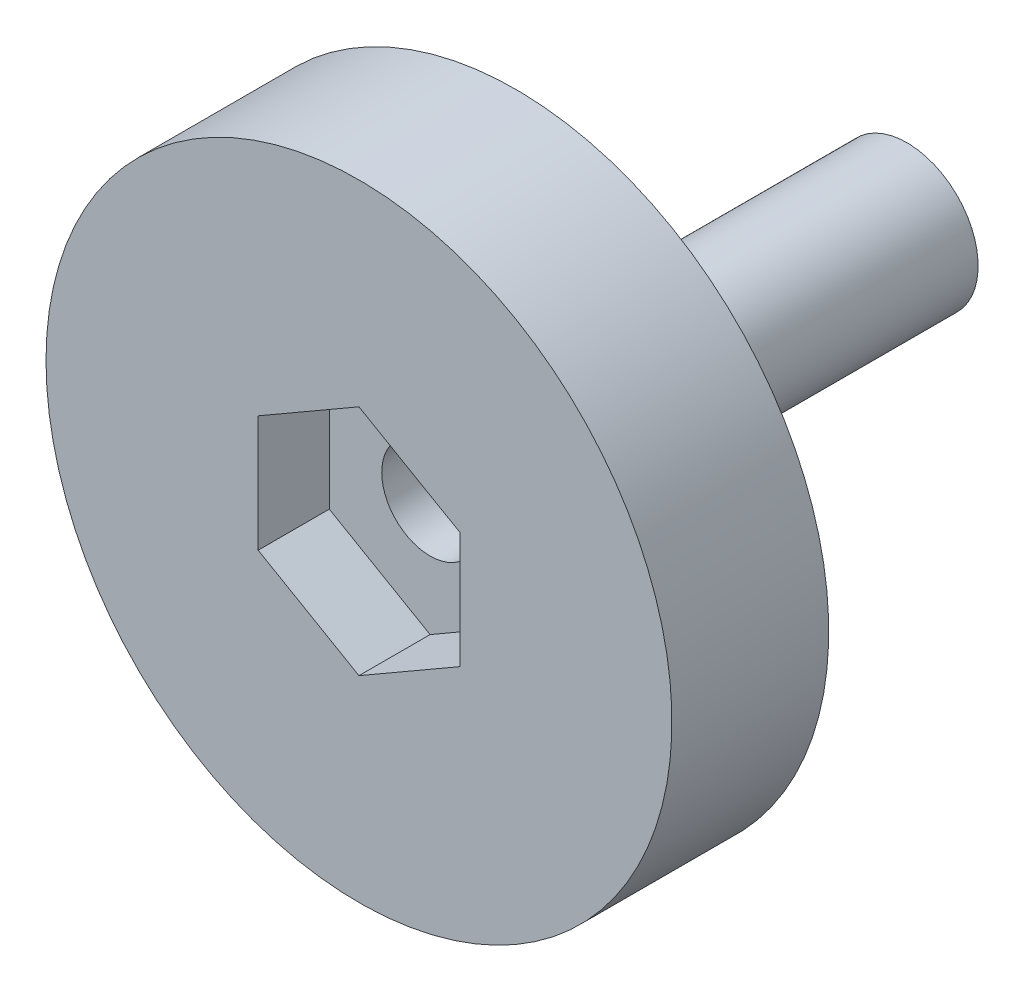
SolidWorks part; units mm, degrees
ref_plane "Front Plane" through (0, 0, 0) normal (0, 0, 1) x (1, 0, 0)
ref_plane "Top Plane" through (0, 0, 0) normal (0, 1, 0) x (1, 0, 0)
ref_plane "Right Plane" through (0, 0, 0) normal (1, 0, 0) x (0, 0, -1)
sketch "Sketch2" plane through (0, 0, 0) normal (0, 1, 0) x (1, 0, 0)
  line L0 (-12.7763, 12.7) -> (-12.7763, 0) construction
  line L1 (-25.4763, 12.7) -> (32.9671, 12.7) construction
  line L2 (-10.6173, 12.7) -> (-9.6013, 12.7)
  line L3 (-10.6173, 12.7) -> (-10.6173, -11.7625)
  line L4 (-10.6173, -11.7625) -> (1.1937, -11.7625)
  line L5 (-9.6013, 12.7) -> (-9.6013, 0)
  line L6 (-9.6013, 0) -> (-6.4263, 0)
  line L7 (1.1937, -4.7625) -> (1.1937, -11.7625)
  line L8 (-6.4263, 0) -> (-6.4263, -4.7625)
  line L9 (-6.4263, -4.7625) -> (1.1937, -4.7625)
  dimension "D1" = 6.35
  dimension "D2" = 4.318
  dimension "D3" = 27.94
  dimension "D4" = 12.7
  dimension "D5" = 7
  dimension "D6" = 4.7625
revolve "Revolve1" add sketch "Sketch2" angle 360 about L0
sketch "Sketch3" plane through (0, 0, 11.7625) normal (0, 0, 1) x (1, 0, 0)
  line L1 (-12.7763, -5.1962) -> (-8.2763, -2.5981)
  line L2 (-8.2763, -2.5981) -> (-8.2763, 2.5981)
  line L3 (-8.2763, 2.5981) -> (-12.7763, 5.1962)
  line L4 (-12.7763, 5.1962) -> (-17.2763, 2.5981)
  line L5 (-17.2763, 2.5981) -> (-17.2763, -2.5981)
  line L6 (-17.2763, -2.5981) -> (-12.7763, -5.1962)
  circle A0 centre (-12.7763, 0) radius 4.5 construction
  dimension "D1" = 9
extrude "Cut-Extrude1" cut sketch "Sketch3" against normal blind 3.175
